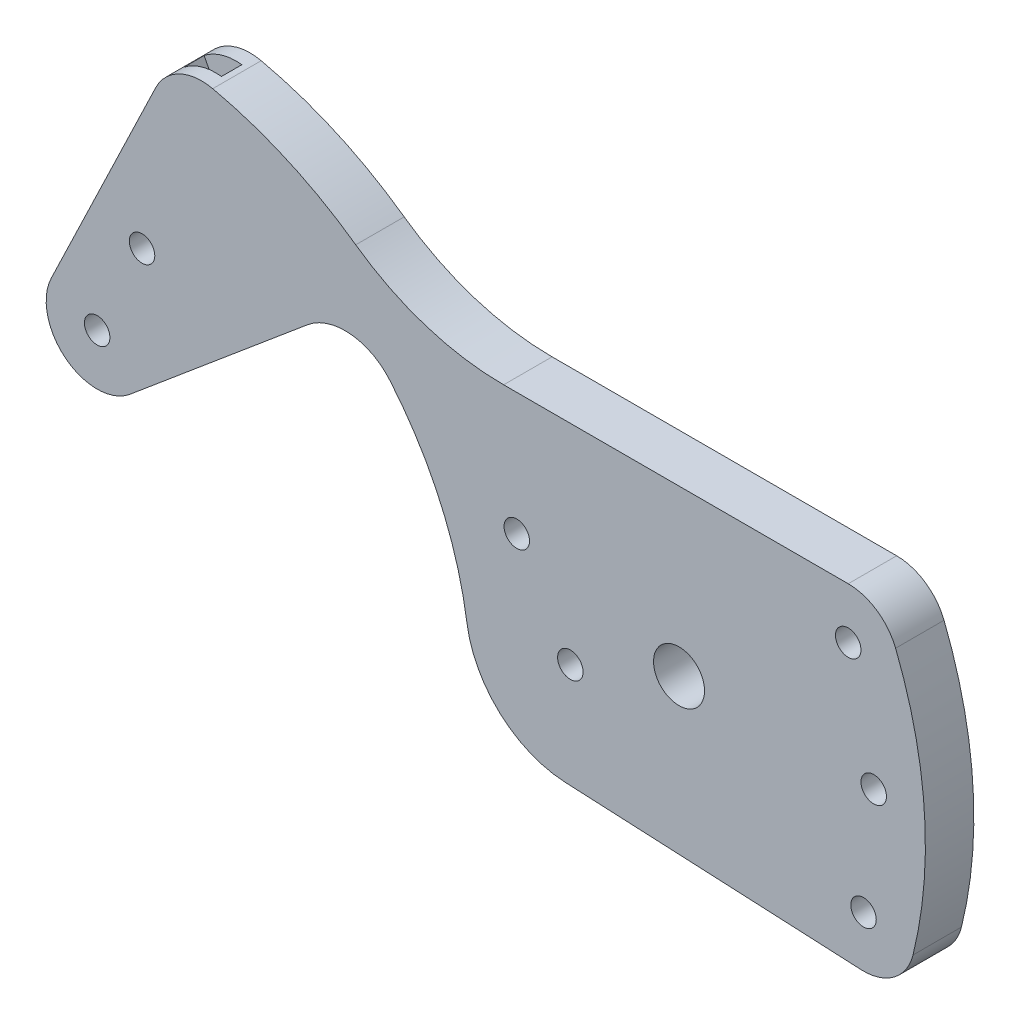
SolidWorks part; units mm, degrees
ref_plane "Front Plane" through (0, 0, 0) normal (0, 0, 1) x (1, 0, 0)
ref_plane "Top Plane" through (0, 0, 0) normal (0, 1, 0) x (1, 0, 0)
ref_plane "Right Plane" through (0, 0, 0) normal (1, 0, 0) x (0, 0, -1)
sketch "Sketch1" plane through (0, 0, 0) normal (0, 0, 1) x (1, 0, 0)
  line L1 (-5, -5) -> (5, -5) construction
  line L2 (-5, -5) -> (-5, 5) construction
  line L3 (-5, 5) -> (5, 5) construction
  line L4 (5, -5) -> (5, 5) construction
  line L5 (-5, -5) -> (5, 5) construction
  line L6 (-5, 5) -> (5, -5) construction
  line L7 (35.6989, -31.9883) -> (-22.3088, -29.1817)
  line L9 (-114.3299, 24.3337) -> (-123.1299, 6.0337)
  line L10 (-107.6899, -5.9604) -> (-72.8648, 23.2613)
  line L11 (-114.3299, 24.3337) -> (-102.6393, 48.6449)
  line L16 (-65.4725, 14.4515) -> (-108.3178, -21.5) construction
  line L17 (50.9822, -33.5) -> (-177.2181, -33.5) construction
  line L20 (-34.3975, 32.3) -> (33.1822, 32.3)
  circle A0 centre (0, 0) radius 5
  circle A1 centre (-31.8178, 8.3) radius 2.5
  circle A2 centre (-21.3178, -8.7) radius 2.5
  circle A3 centre (33.1822, 22.3) radius 2.5
  circle A4 centre (38.1822, -0.1) radius 2.5
  circle A5 centre (36.1822, -22) radius 2.5
  circle A6 centre (36.1822, -22) radius 2.5 construction
  circle A7 centre (38.1822, -0.1) radius 2.5 construction
  circle A8 centre (33.1822, 22.3) radius 2.5 construction
  circle A9 centre (-31.8178, 8.3) radius 2.5 construction
  circle A10 centre (-21.3178, -8.7) radius 2.5 construction
  arc A12 (-41.605, -11.6848) -> (-22.3088, -29.1817) centre (-21.3178, -8.7) ccw
  arc A13 (32.976, -31.8566) -> (28.2895, 32.3) centre (-34.3029, -4.5217) ccw construction
  arc A14 (45.8883, -24.4068) -> (42.4751, 25.9934) centre (-34.3029, -4.5217) ccw
  arc A15 (35.6989, -31.9883) -> (45.8883, -24.4068) centre (36.1822, -22) ccw
  arc A16 (42.4751, 25.9934) -> (33.1822, 32.3) centre (33.1822, 22.3) ccw
  circle A17 centre (-105.3178, 20) radius 2.5
  circle A18 centre (-34.3029, -4.5217) radius 82.6199 construction
  circle A19 centre (-114.1178, 1.7) radius 2.5
  circle A21 centre (-105.3178, 20) radius 2.5 construction
  circle A22 centre (-114.1178, 1.7) radius 2.5 construction
  circle A23 centre (-105.3178, 20) radius 10 construction
  arc A24 (-123.1299, 6.0337) -> (-107.6899, -5.9604) centre (-114.1178, 1.7) ccw
  arc A27 (-91.4485, 54.071) -> (-102.6393, 48.6449) centre (-93.6271, 44.3112) ccw
  circle A31 centre (-34.3029, -4.5217) radius 72.6199 construction
  arc A32 (-41.605, -11.6848) -> (-56.6627, 21.8438) centre (-108.3178, -21.5) ccw
  arc A33 (-31.0644, -26.7412) -> (-91.4485, 54.071) centre (-108.3178, -21.5) ccw
  arc A34 (-63.4016, 41.5721) -> (-34.3975, 32.3) centre (-34.3975, 82.3) ccw
  arc A35 (-56.6627, 21.8438) -> (-72.8648, 23.2613) centre (-65.4725, 14.4515) ccw
  circle A36 centre (-65.4725, 14.4515) radius 10.5004 construction
  circle A37 centre (-108.3178, -21.5) radius 67.4309 construction
  circle A38 centre (-108.3178, -21.5) radius 77.4309 construction
  circle A39 centre (-108.3178, -21.5) radius 10.5004 construction
  circle A40 centre (-108.3178, -21.5) radius 11.5004 construction
  circle A41 centre (0, 0) radius 33 construction
  point P35 (50.3427, -4.5217)
  point P37 (37.1696, 16.7103)
  point P54 (-36.0565, -0.0269)
  point P75 (-40.8381, -1.4887)
  dimension "D1" = 10
  dimension "D3" = 10
  dimension "D5" = 50
  dimension "D7" = 40
  dimension "D4" = 10
  dimension "D2" = 10
  dimension "D8" = 1
extrude "Boss-Extrude1" add sketch "Sketch1" along normal mid plane 9.5 contours A0 L4 L3 | A0 L1 L4 | A0 L2 L1 | A0 L3 L2 | A35 A32 A12 A33 A27 L11 L9 A24 L10 A17 A19
sketch "Sketch2" plane through (0, 0, 0) normal (0, 0, 1) x (1, 0, 0)
  line L0 (-93.6271, 44.3112) -> (-96.4023, 53.9184) construction
  line L1 (-78.2271, 18.7618) -> (-72.8648, 23.2613)
  line L2 (-93.6271, 44.3112) -> (-84.6823, 13.3452) construction
  line L3 (-91.6689, 44.8769) -> (-78.2271, 18.7618)
  line L4 (-94.4967, 54.2733) -> (-93.6271, 44.3112) construction
  line L5 (-93.6271, 44.3112) -> (-90.4984, 8.4649) construction
  line L6 (-98.2036, 53.2026) -> (-93.6271, 44.3112) construction
  line L7 (-93.6271, 44.3112) -> (-79.798, 17.4436) construction
  line L8 (-99.8894, 52.1076) -> (-95.5854, 43.7456)
  line L9 (-92.4867, 54.246) -> (-91.6689, 44.8769)
  line L12 (-92.369, 6.8953) -> (-78.2271, 18.7618)
  line L13 (-107.6899, -5.9604) -> (-72.8648, 23.2613) construction
  line L14 (-100.8204, 53.9163) -> (-90.7503, 34.3517) construction
  line L15 (-92.6635, 56.2725) -> (-90.7503, 34.3517) construction
  line L16 (-95.5854, 43.7456) -> (-92.369, 6.8953)
  line L18 (-96.504, 54.2707) -> (-78.2271, 18.7618) construction
  line L19 (-96.504, 54.2707) -> (-92.369, 6.8953) construction
  line L20 (-92.369, 6.8953) -> (-107.6899, -5.9604)
  line L22 (-93.6271, 44.3112) -> (-90.3766, 7.0692) construction
  line L23 (-93.6271, 44.3112) -> (-80.0054, 17.8465) construction
  arc A0 (-92.4867, 54.246) -> (-99.8894, 52.1076) centre (-93.6271, 44.3112) ccw
  arc A1 (-94.4967, 54.2733) -> (-98.2036, 53.2026) centre (-93.6271, 44.3112) ccw construction
  arc A2 (-92.6635, 56.2725) -> (-100.8204, 53.9163) centre (-93.6271, 44.3112) ccw construction
  arc A3 (-91.4485, 54.071) -> (-102.6393, 48.6449) centre (-93.6271, 44.3112) ccw construction
  point P33 (-96.4023, 53.9184)
  dimension "D3" = 7
  dimension "D4" = 20
  dimension "D1" = 2
  dimension "D2" = 2
extrude "Cut-Extrude1" cut sketch "Sketch2" against normal mid plane 4
